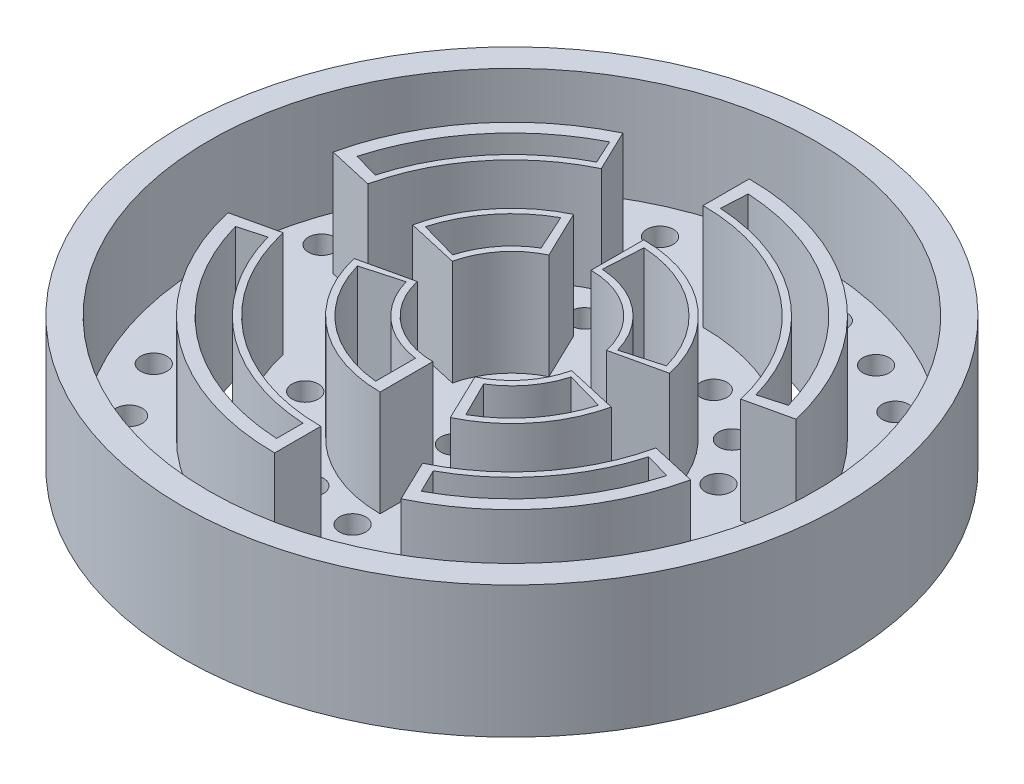
SolidWorks part; units mm, degrees
ref_plane "Front Plane" through (0, 0, 0) normal (0, 0, 1) x (1, 0, 0)
ref_plane "Top Plane" through (0, 0, 0) normal (0, 1, 0) x (1, 0, 0)
ref_plane "Right Plane" through (0, 0, 0) normal (1, 0, 0) x (0, 0, -1)
sketch "Sketch1" plane through (0, 0, 0) normal (0, 1, 0) x (1, 0, 0)
  circle A0 centre (0, 0) radius 63.5
  circle A1 centre (0, 0) radius 38.1
  circle A2 centre (0, 0) radius 12.7
  dimension "D1" = 127
  dimension "D2" = 25.4
  dimension "D3" = 25.4
extrude "Boss-Extrude1" add sketch "Sketch1" along normal blind 25.4 contours A0 A1 | A1 A2 | A2
sketch "Sketch2" plane through (0, 25.4, 0) normal (0, 1, 0) x (1, 0, 0)
  line L0 (0, 15.24) -> (0, 25.4)
  line L2 (0, -15.24) -> (0, -25.4)
  line L3 (14.8611, 3.377) -> (24.7686, 5.6283)
  line L4 (-44.5834, 10.131) -> (-35.9144, 8.1611)
  line L5 (-44.5834, -10.131) -> (-35.9144, -8.1611)
  line L6 (-19.8271, 41.1971) -> (-15.9718, 33.1866)
  line L7 (0, -36.83) -> (0, -45.72)
  line L8 (-24.7686, -5.6283) -> (-14.8611, -3.377)
  line L9 (-24.7686, 5.6283) -> (-14.8611, 3.377)
  line L11 (15.9718, -33.1866) -> (19.8271, -41.1971)
  line L12 (35.9144, -8.1611) -> (44.5834, -10.131)
  line L13 (35.9144, 8.1611) -> (44.5834, 10.131)
  line L14 (0, 36.83) -> (0, 45.72)
  line L15 (-11.0151, 22.8873) -> (-6.609, 13.7324)
  line L16 (14.8611, -3.377) -> (24.7686, -5.6283)
  line L17 (6.609, -13.7324) -> (11.0151, -22.8873)
  circle A0 centre (0, 0) radius 58.42
  arc A1 (-44.5834, -10.131) -> (0, -45.72) centre (0, 0) ccw
  arc A2 (-35.9144, -8.1611) -> (0, -36.83) centre (0, 0) ccw
  arc A3 (-24.7686, -5.6283) -> (0, -25.4) centre (0, 0) ccw
  arc A4 (-15.9718, 33.1866) -> (-35.9144, 8.1611) centre (0, 0) ccw
  arc A5 (-19.8271, 41.1971) -> (-44.5834, 10.131) centre (0, 0) ccw
  arc A6 (35.9144, 8.1611) -> (0, 36.83) centre (0, 0) ccw
  arc A7 (44.5834, 10.131) -> (0, 45.72) centre (0, 0) ccw
  arc A8 (15.9718, -33.1866) -> (35.9144, -8.1611) centre (0, 0) ccw
  arc A9 (19.8271, -41.1971) -> (44.5834, -10.131) centre (0, 0) ccw
  arc A10 (-14.8611, -3.377) -> (0, -15.24) centre (0, 0) ccw
  arc A11 (11.0151, -22.8873) -> (24.7686, -5.6283) centre (0, 0) ccw
  arc A12 (6.609, -13.7324) -> (14.8611, -3.377) centre (0, 0) ccw
  arc A13 (-6.609, 13.7324) -> (-14.8611, 3.377) centre (0, 0) ccw
  arc A14 (-11.0151, 22.8873) -> (-24.7686, 5.6283) centre (0, 0) ccw
  arc A15 (14.8611, 3.377) -> (0, 15.24) centre (0, 0) ccw
  arc A16 (24.7686, 5.6283) -> (0, 25.4) centre (0, 0) ccw
extrude "Cut-Extrude3" cut sketch "Sketch2" against normal blind 20.32
sketch "Sketch3" plane through (0, 25.4, 0) normal (0, 1, 0) x (1, 0, 0)
  line L0 (-41.5605, 11.7149) -> (-36.671, 10.3367)
  line L1 (-19.6289, 38.4606) -> (-17.5156, 33.8351)
  line L2 (2.411, 43.1126) -> (2.1273, 38.0406)
  line L3 (41.5605, 11.7149) -> (36.671, 10.3367)
  line L4 (-41.5605, -11.7149) -> (-36.671, -10.3367)
  line L5 (-2.2368, -43.122) -> (-2.2368, -38.0343)
  line L6 (8.6282, -14.076) -> (12.0325, -20.9159)
  line L7 (15.8908, -4.4792) -> (23.225, -6.5466)
  line L8 (-23.225, 6.5466) -> (-15.8908, 4.4792)
  line L9 (-11.6991, 21.1042) -> (-8.5185, 14.1427)
  line L10 (1.3473, 24.0924) -> (0.9218, 16.4842)
  line L11 (23.225, 6.5466) -> (15.8908, 4.4792)
  line L12 (36.671, -10.3367) -> (41.5605, -11.7149)
  line L13 (18.2643, -33.4369) -> (20.5292, -37.9877)
  line L14 (-2.2368, -24.0261) -> (-2.2368, -16.3578)
  line L15 (-23.225, -6.5466) -> (-15.8908, -4.4792)
  arc A0 (-41.5605, -11.7149) -> (-2.2368, -43.122) centre (0, 0) ccw
  arc A1 (-36.671, -10.3367) -> (-2.2368, -38.0343) centre (0, 0) ccw
  arc A2 (-23.225, -6.5466) -> (-2.2368, -24.0261) centre (0, 0) ccw
  arc A3 (-15.8908, -4.4792) -> (-2.2368, -16.3578) centre (0, 0) ccw
  arc A4 (-11.6991, 21.1042) -> (-23.225, 6.5466) centre (0, 0) ccw
  arc A5 (-8.5185, 14.1427) -> (-15.8908, 4.4792) centre (0, 0) ccw
  arc A6 (-17.5156, 33.8351) -> (-36.671, 10.3367) centre (0, 0) ccw
  arc A7 (-19.6289, 38.4606) -> (-41.5605, 11.7149) centre (0, 0) ccw
  arc A8 (23.225, 6.5466) -> (1.3473, 24.0924) centre (0, 0) ccw
  arc A9 (15.8908, 4.4792) -> (0.9218, 16.4842) centre (0, 0) ccw
  arc A10 (36.671, 10.3367) -> (2.1273, 38.0406) centre (0, 0) ccw
  arc A11 (41.5605, 11.7149) -> (2.411, 43.1126) centre (0, 0) ccw
  arc A12 (12.0325, -20.9159) -> (23.225, -6.5466) centre (0, 0) ccw
  arc A13 (8.6282, -14.076) -> (15.8908, -4.4792) centre (0, 0) ccw
  arc A14 (18.2643, -33.4369) -> (36.671, -10.3367) centre (0, 0) ccw
  arc A15 (20.5292, -37.9877) -> (41.5605, -11.7149) centre (0, 0) ccw
extrude "Cut-Extrude4" cut sketch "Sketch3" against normal blind 25.4
sketch "Sketch4" plane through (0, 5.08, 0) normal (0, 1, 0) x (1, 0, 0)
  circle A1 centre (-1.7242, 51.4928) radius 2.54
  circle A2 centre (11.4555, 50.5546) radius 2.54
  circle A3 centre (22.9899, 47.1688) radius 2.54
  circle A4 centre (32.6236, 41.2546) radius 2.54
  circle A5 centre (40.612, 33.1299) radius 2.54
  circle A6 centre (46.8898, 22.0622) radius 2.54
  circle A7 centre (0.945, 29.823) radius 2.54
  circle A8 centre (11.4555, 27.4253) radius 2.54
  circle A9 centre (21.4931, 20.8907) radius 2.54
  circle A10 centre (27.6494, 12.1427) radius 2.54
  circle A11 centre (4.4709, 6.7036) radius 2.54
  circle A12 centre (-6.8008, 4.3217) radius 2.54
  circle A13 centre (-30.1981, -0.0817) radius 2.54
  circle A14 centre (-28.1073, 10.409) radius 2.54
  circle A15 centre (-21.5717, 20.4459) radius 2.54
  circle A16 centre (-12.9298, 26.8909) radius 2.54
  circle A17 centre (-51.8067, 1.2055) radius 2.54
  circle A18 centre (-50.5434, 13.8668) radius 2.54
  circle A19 centre (-46.525, 24.5288) radius 2.54
  circle A20 centre (-40.1077, 33.8349) radius 2.54
  circle A21 centre (-30.9292, 41.5978) radius 2.54
  circle A22 centre (-19.256, 47.788) radius 2.54
  circle A23 centre (1.8396, -51.4888) radius 2.54
  circle A24 centre (-11.3421, -50.5801) radius 2.54
  circle A25 centre (-22.8841, -47.2202) radius 2.54
  circle A26 centre (-32.531, -41.3276) radius 2.54
  circle A27 centre (-40.5377, -33.2209) radius 2.54
  circle A28 centre (-46.8402, -22.1673) radius 2.54
  circle A29 centre (-0.8781, -29.825) radius 2.54
  circle A30 centre (-11.394, -27.4509) radius 2.54
  circle A31 centre (-21.4462, -20.9388) radius 2.54
  circle A32 centre (-27.6221, -12.2047) radius 2.54
  circle A33 centre (-4.4558, -6.7137) radius 2.54
  circle A34 centre (6.8105, -4.3064) radius 2.54
  circle A35 centre (30.1979, 0.1494) radius 2.54
  circle A36 centre (28.1306, -10.346) radius 2.54
  circle A37 centre (21.6175, -20.3975) radius 2.54
  circle A38 centre (12.9901, -26.8619) radius 2.54
  circle A39 centre (51.8093, -1.0894) radius 2.54
  circle A40 centre (50.5744, -13.7535) radius 2.54
  circle A41 centre (46.5799, -24.4244) radius 2.54
  circle A42 centre (40.1835, -33.7449) radius 2.54
  circle A43 centre (31.0224, -41.5283) radius 2.54
  circle A44 centre (19.3631, -47.7447) radius 2.54
  point P28 (21.4931, 20.8907)
  point P29 (11.4555, 27.4253)
extrude "Cut-Extrude5" cut sketch "Sketch4" against normal blind 25.4
